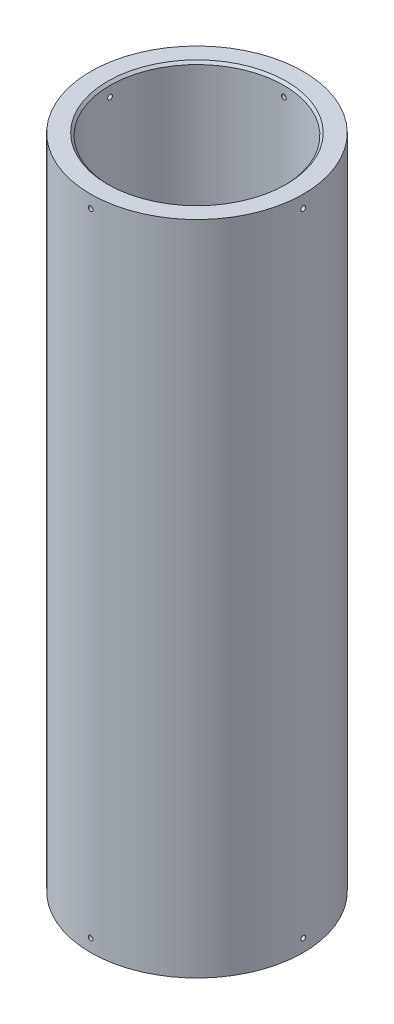
SolidWorks part; units mm, degrees
ref_plane "Plano frontal" through (0, 0, 0) normal (0, 0, 1) x (1, 0, 0)
ref_plane "Plano superior" through (0, 0, 0) normal (0, 1, 0) x (1, 0, 0)
ref_plane "Plano direito" through (0, 0, 0) normal (1, 0, 0) x (0, 0, -1)
sketch "Esboço1" plane through (0, 0, 0) normal (0, 1, 0) x (1, 0, 0)
  circle A0 centre (0, 0) radius 44.5
  circle A1 centre (0, 0) radius 36.4
  dimension "D1" = 89
  dimension "D2" = 8.1
extrude "Ressalto-extrusão1" add sketch "Esboço1" along normal blind 275
chamfer "Chanfro1" distance 1 angle 45 2 edges at (0, 0, 36.4) (0, 275, 36.4)
ref_plane "Plano2" through (0, 0, 44.5) normal (0, 0, 1) x (1, 0, 0)
sketch "Esboço5" plane through (0, 0, 44.5) normal (0, 0, 1) x (1, 0, 0)
  line L0 (0, 275) -> (0, 269.75) construction
  line L1 (44.5, 275) -> (-44.5, 275) construction
  line L2 (44.5, 137.5) -> (-44.5, 137.5) construction
  line L3 (44.5, 0) -> (44.5, 275) construction
  line L4 (-44.5, 275) -> (-44.5, 0) construction
  line L5 (0, 0) -> (0, 5.25) construction
  line L6 (-44.5, 0) -> (44.5, 0) construction
  line L7 (0, 5.25) -> (1, 5.25) construction
  line L8 (0, 269.75) -> (1, 269.75) construction
  circle A0 centre (0, 5.25) radius 1
  circle A1 centre (0, 269.75) radius 1
  dimension "D2" = 2
  dimension "D4" = 2
  dimension "D1" = 5.25
  dimension "D3" = 5.25
extrude "Corte-extrusão3" cut sketch "Esboço5" against normal through all contours A1 | A0
cosmetic thread "Representação de rosca2" parameters "D2"=3
cosmetic thread "Representação de rosca4" parameters "D2"=3
cosmetic thread "Representação de rosca6" parameters "D2"=3
cosmetic thread "Representação de rosca8" parameters "D2"=3
ref_plane "Plano5" through (-44.5, 0, 0) normal (-1, 0, 0) x (0, 0, 1)
sketch "Esboço13" plane through (-44.5, 0, 0) normal (-1, 0, 0) x (0, 0, 1)
  line L0 (0, 0) -> (0, 5.25) construction
  line L1 (-44.5, 0) -> (44.5, 0) construction
  line L2 (0, 5.25) -> (1, 5.25) construction
  line L3 (0, 275) -> (0, 269.75) construction
  line L6 (44.5, 275) -> (-44.5, 275) construction
  circle A0 centre (0, 5.25) radius 1
  circle A2 centre (0, 269.75) radius 1
  dimension "D1" = 2
  dimension "D3" = 2
  dimension "D2" = 5.25
  dimension "D4" = 5.25
extrude "Corte-extrusão4" cut sketch "Esboço13" against normal through all
cosmetic thread "Representação de rosca1" parameters "D2"=3
cosmetic thread "Representação de rosca3" parameters "D2"=3
cosmetic thread "Representação de rosca5" parameters "D2"=3
cosmetic thread "Representação de rosca7" parameters "D2"=3
equation "\"dim_ext\"= 89"
equation "\"exp_wal\"= 8.1"
equation "\"len_total\"= 250"
